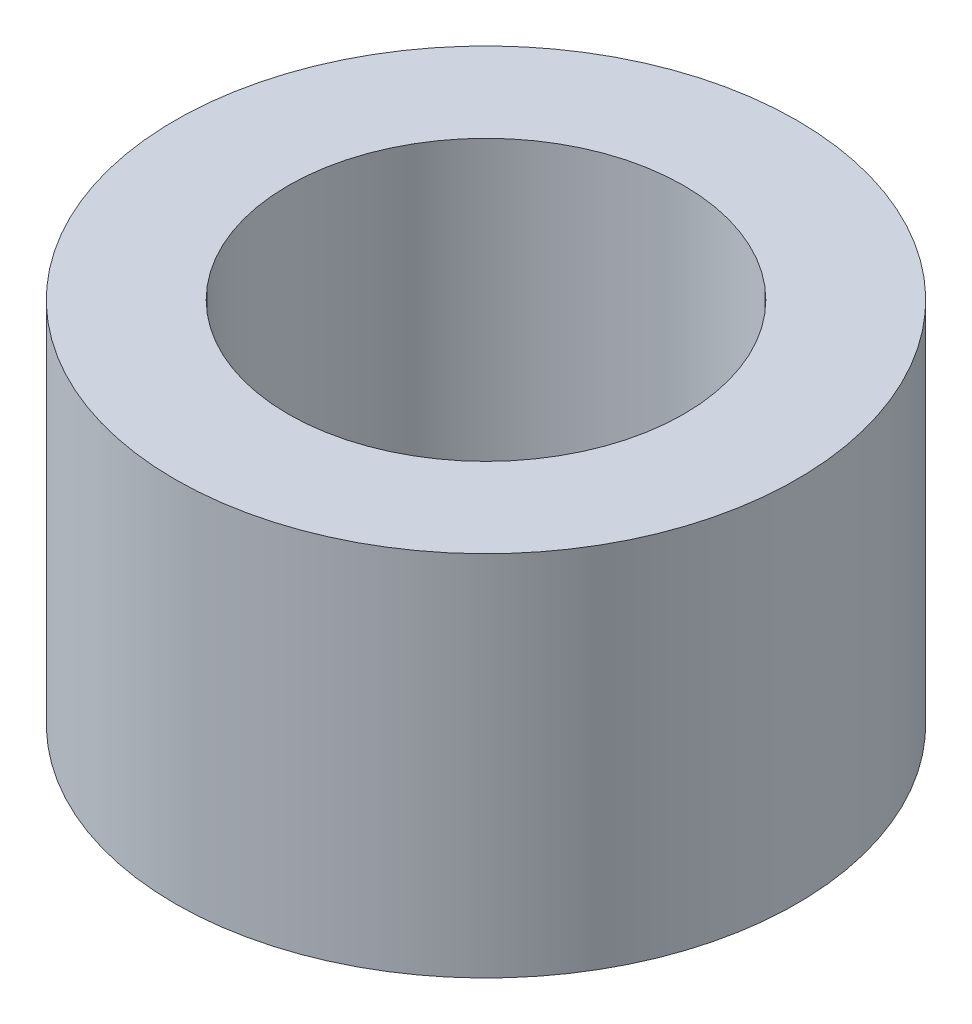
SolidWorks part; units mm, degrees
ref_plane "Alzado" through (0, 0, 0) normal (0, 0, 1) x (1, 0, 0)
ref_plane "Planta" through (0, 0, 0) normal (0, 1, 0) x (1, 0, 0)
ref_plane "Vista lateral" through (0, 0, 0) normal (1, 0, 0) x (0, 0, -1)
sketch "Croquis1" plane through (0, 0, 0) normal (0, 1, 0) x (1, 0, 0)
  circle A0 centre (0, 0) radius 7
  circle A1 centre (0, 0) radius 11
  dimension "D1" = 22
  dimension "D2" = 14
extrude "Saliente-Extruir1" add sketch "Croquis1" along normal blind 13
